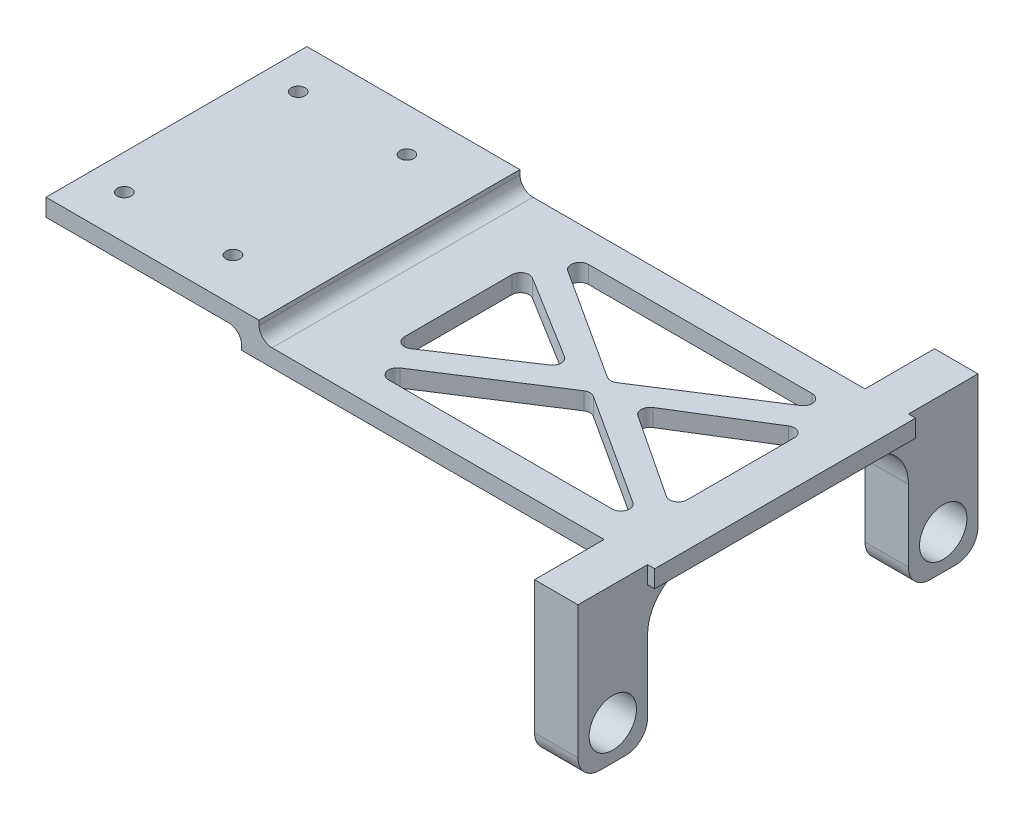
SolidWorks part; units mm, degrees
ref_plane "Front Plane" through (0, 0, 0) normal (0, 0, 1) x (1, 0, 0)
ref_plane "Top Plane" through (0, 0, 0) normal (0, 1, 0) x (1, 0, 0)
ref_plane "Right Plane" through (0, 0, 0) normal (1, 0, 0) x (0, 0, -1)
sketch "Sketch1" plane through (0, 0, 0) normal (0, 0, 1) x (1, 0, 0)
  line L0 (-37.9394, 0.8854) -> (7.0606, 0.8854)
  line L1 (7.0606, 0.8854) -> (7.0606, -3.1146)
  line L2 (7.0606, -3.1146) -> (102.0606, -3.1146)
  line L3 (102.0606, -3.1146) -> (102.0606, 0.8854)
  line L4 (102.0606, 0.8854) -> (11.0606, 0.8854)
  line L5 (11.0606, 0.8854) -> (11.0606, 4.8854)
  line L6 (11.0606, 4.8854) -> (-37.9394, 4.8854)
  line L7 (-37.9394, 4.8854) -> (-37.9394, 0.8854)
  dimension "D1" = 4
  dimension "D2" = 45
  dimension "D3" = 95
  dimension "D4" = 4
  dimension "D5" = 4
  dimension "D6" = 4
extrude "Boss-Extrude1" add sketch "Sketch1" along normal blind 60
fillet "Fillet1" radius 3 2 edges at (7.0606, 0.8854, 30) (11.0606, 0.8854, 30)
sketch "Sketch2" plane through (0, 4.8854, 0) normal (0, 1, 0) x (1, 0, 0)
  line L0 (11.0606, -60) -> (11.0606, 0) construction
  line L1 (11.0606, -60) -> (-37.9394, -60) construction
  line L2 (-4.9394, -50) -> (-40.5826, -50) construction
  line L4 (-37.9394, -30) -> (15.1931, -30) construction
  line L5 (-37.9394, -60) -> (-37.9394, 0) construction
  circle A0 centre (-4.9394, -50) radius 1.6
  circle A4 centre (-29.9394, -50) radius 1.6
  dimension "D1" = 3.2
  dimension "D2" = 16
  dimension "D3" = 10
  dimension "D4" = 3.2
  dimension "D5" = 25
extrude "Cut-Extrude1" cut sketch "Sketch2" against normal up to next
ref_plane "Plane1" through (0, 0, 30) normal (0, 0, 1) x (1, 0, 0)
mirror "Mirror2" about plane through (0, 0, 30) normal (0, 0, 1) of "Cut-Extrude1"
sketch "Sketch4" plane through (0, 0.8854, 0) normal (0, 1, 0) x (1, 0, 0)
  line L0 (27.0606, -14.2762) -> (27.0606, -46.2762)
  line L1 (27.0606, -46.2762) -> (52.0606, -29.744)
  line L2 (52.0606, -29.744) -> (27.0606, -14.2762)
  line L3 (59.5606, -32) -> (27.0606, -53)
  line L4 (27.0606, -53) -> (92.0606, -53)
  line L5 (92.0606, -53) -> (59.5606, -32)
  line L6 (102.0606, -60) -> (102.0606, 0) construction
  line L7 (59.5606, -32) -> (59.5606, 12.902) construction
  line L8 (67.0606, -29.744) -> (92.0606, -14.2762)
  line L9 (92.0606, -46.2762) -> (67.0606, -29.744)
  line L10 (92.0606, -14.2762) -> (92.0606, -46.2762)
  line L11 (-4.4, -30) -> (4.4, -30) construction
  line L12 (92.0606, -7) -> (59.5606, -28)
  line L13 (27.0606, -7) -> (92.0606, -7)
  line L14 (59.5606, -28) -> (27.0606, -7)
  line L15 (102.0606, -60) -> (14.0606, -60) construction
  point P7 (59.5606, -53)
  dimension "D1" = 21
  dimension "D2" = 32
  dimension "D3" = 25
  dimension "D4" = 10
  dimension "D5" = 65
  dimension "D6" = 50
  dimension "D7" = 7
extrude "Cut-Extrude2" cut sketch "Sketch4" against normal up to next
fillet "Fillet2" radius 2 12 edges at (92.0606, -1.1146, 46.2762) (67.0606, -1.1146, 29.744) (92.0606, -1.1146, 14.2762) (92.0606, -1.1146, 7) (59.5606, -1.1146, 28) (27.0606, -1.1146, 7) (59.5606, -1.1146, 32) (92.0606, -1.1146, 53) (52.0606, -1.1146, 29.744) (27.0606, -1.1146, 14.2762) (27.0606, -1.1146, 46.2762) (27.0606, -1.1146, 53)
sketch "Sketch5" plane through (0, 0, 60) normal (0, 0, 1) x (1, 0, 0)
  line L1 (100.4229, 0.8854) -> (90.4229, 0.8854)
  line L2 (100.4229, 0.8854) -> (100.4229, -3.1146)
  line L3 (100.4229, -3.1146) -> (90.4229, -3.1146)
  line L4 (90.4229, 0.8854) -> (90.4229, -3.1146)
  line L5 (7.0606, -3.1146) -> (102.0606, -3.1146) construction
  line L6 (102.0606, 0.8854) -> (14.0606, 0.8854) construction
  dimension "D1" = 10
extrude "Boss-Extrude2" add sketch "Sketch5" along normal blind 16
sketch "Sketch6" plane through (0, -3.1146, 0) normal (0, -1, 0) x (1, 0, 0)
  line L0 (100.4229, 76) -> (100.4229, 60) construction
  line L1 (90.4229, 76) -> (100.4229, 76)
  line L2 (90.4229, 76) -> (90.4229, 60)
  line L3 (90.4229, 60) -> (100.4229, 60)
  line L4 (100.4229, 76) -> (100.4229, 60)
  line L5 (90.4229, 76) -> (100.4229, 76) construction
  line L6 (90.4229, 76) -> (90.4229, 60) construction
  line L7 (7.0606, 60) -> (90.4229, 60) construction
extrude "Boss-Extrude3" add sketch "Sketch6" along normal blind 31.5
sketch "Sketch7" plane through (100.4229, 0, 0) normal (1, 0, 0) x (0, 0, -1)
  line L0 (-76, -34.6146) -> (-76, 0.8854) construction
  line L1 (-60, -34.6146) -> (-76, -34.6146) construction
  circle A0 centre (-68, -26.6146) radius 5.45
  dimension "D1" = 10.9
  dimension "D2" = 8
  dimension "D3" = 8
extrude "Cut-Extrude3" cut sketch "Sketch7" against normal up to next
fillet "Fillet3" radius 5 2 edges at (95.4229, -34.6146, 76) (95.4229, -34.6146, 60)
fillet "Fillet4" radius 10 1 edges at (95.4229, -3.1146, 60)
mirror "Mirror3" about plane through (0, 0, 30) normal (0, 0, 1) of "Fillet3", "Cut-Extrude3", "Fillet4", "Boss-Extrude3", "Boss-Extrude2"
